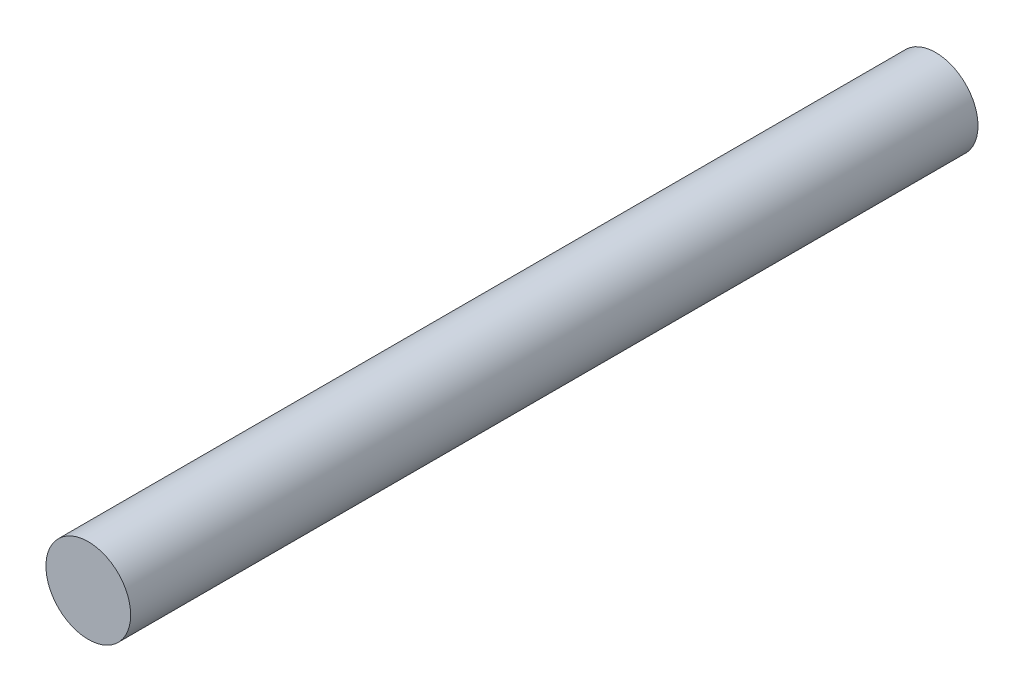
SolidWorks part; units mm, degrees
ref_plane "前视基准面" through (0, 0, 0) normal (0, 0, 1) x (1, 0, 0)
ref_plane "上视基准面" through (0, 0, 0) normal (0, 1, 0) x (1, 0, 0)
ref_plane "右视基准面" through (0, 0, 0) normal (1, 0, 0) x (0, 0, -1)
other "Configuration Table"
sketch "草图1" plane through (0, 0, 0) normal (0, 0, 1) x (1, 0, 0)
  circle A0 centre (0, 0) radius 5
  dimension "D1" = 10
extrude "凸台-拉伸1" add sketch "草图1" along normal blind 100
